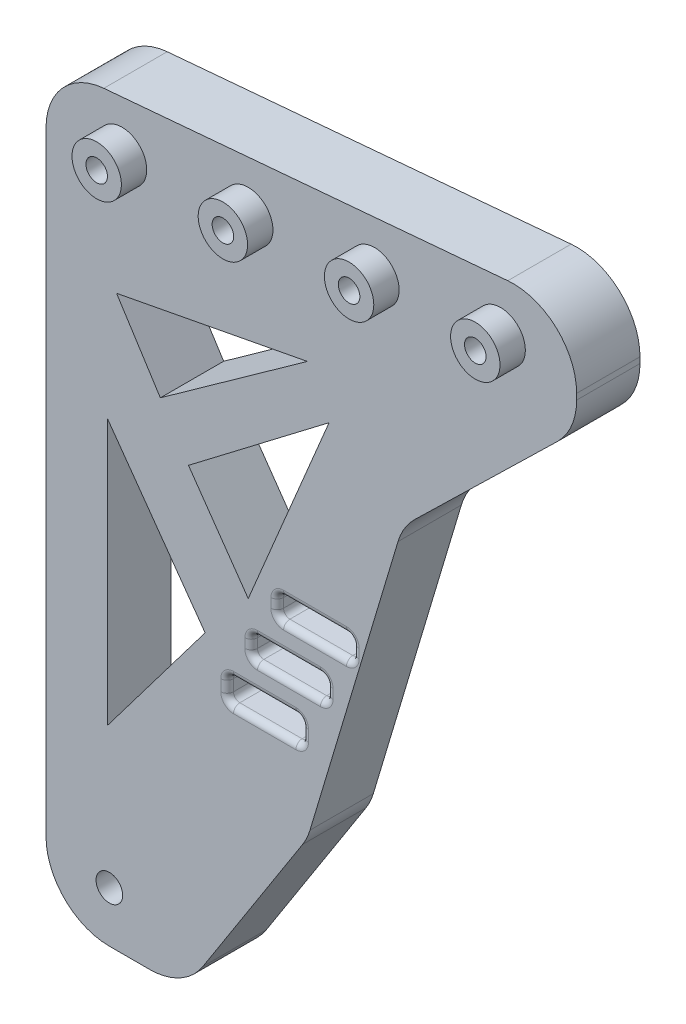
SolidWorks part; units mm, degrees
ref_plane "Front Plane" through (0, 0, 0) normal (0, 0, 1) x (1, 0, 0)
ref_plane "Top Plane" through (0, 0, 0) normal (0, 1, 0) x (1, 0, 0)
ref_plane "Right Plane" through (0, 0, 0) normal (1, 0, 0) x (0, 0, -1)
sketch "草圖1" plane through (0, 0, 0) normal (0, 0, 1) x (1, 0, 0)
  line L0 (0, 0) -> (59.7717, 5.2293) construction
  line L1 (0, 0) -> (0, 23.9784) construction
  line L2 (-12, 6.9807) -> (-12, -9.0804)
  line L3 (-12, 6.9807) -> (71.7717, 14.3098)
  line L4 (-12, -9.0804) -> (71.7717, -1.7514)
  line L5 (71.7717, 14.3098) -> (71.7717, -1.7514)
  line L6 (-12, -9.0804) -> (-12, -109.0804)
  line L7 (-12, -109.0804) -> (9.8062, -109.0804)
  line L8 (9.8062, -109.0804) -> (29.2699, -78.7271)
  line L9 (29.2699, -78.7271) -> (44.3137, -28.4865)
  line L10 (44.3137, -28.4865) -> (71.7717, -1.7514)
  line L11 (-0.8625, -19.2433) -> (29.2699, -13.4935)
  line L12 (29.2699, -13.4935) -> (6.0482, -30.0804)
  line L13 (6.0482, -30.0804) -> (-0.8625, -19.2433)
  line L14 (-2.2999, -37.0882) -> (13.1171, -58.6721)
  line L15 (13.1171, -58.6721) -> (-2.2999, -79.0539)
  line L16 (-2.2999, -79.0539) -> (-2.2999, -37.0882)
  line L23 (20.3863, -58.6721) -> (32.3185, -58.6721)
  line L24 (32.3185, -58.6721) -> (32.3185, -55.2145)
  line L25 (32.3185, -55.2145) -> (20.3863, -55.2145)
  line L26 (20.3863, -55.2145) -> (20.3863, -58.6721)
  line L27 (16.5956, -62.7059) -> (28.4375, -62.7059)
  line L28 (28.4375, -62.7059) -> (28.4375, -66.4979)
  line L29 (28.4375, -66.4979) -> (16.5956, -66.4979)
  line L30 (16.5956, -66.4979) -> (16.5956, -62.7059)
  line L31 (10.4915, -37.0882) -> (32.6885, -20.1617)
  line L32 (32.6885, -20.1617) -> (19.9239, -50.5901)
  line L33 (19.9239, -50.5901) -> (10.4915, -37.0882)
  line L34 (24.5027, -51.1166) -> (36.4348, -51.1166)
  line L35 (36.4348, -51.1166) -> (36.4348, -47.6589)
  line L36 (36.4348, -47.6589) -> (24.5027, -47.6589)
  line L37 (24.5027, -47.6589) -> (24.5027, -51.1166)
  circle A0 centre (0, 0) radius 3.9
  circle A1 centre (19.9239, 1.7431) radius 3.9
  circle A2 centre (39.8478, 3.4862) radius 3.9
  circle A3 centre (59.7717, 5.2293) radius 3.9
  circle A4 centre (-2, -101.0804) radius 2.1
  point P36 (32.6885, -20.1617)
  point P38 (19.9239, -50.5901)
  dimension "D2" = 7.8
  dimension "D12" = 4.2
  dimension "D1" = 85
  dimension "D3" = 20
  dimension "D4" = 20
  dimension "D5" = 20
  dimension "D6" = 8
  dimension "D7" = 8
  dimension "D8" = 85
  dimension "D9" = 12
  dimension "D10" = 12
  dimension "D11" = 100
  dimension "D13" = 8
  dimension "D14" = 10
extrude "填料-伸長1" add sketch "草圖1" along normal blind 10
fillet "圓角1" radius 10 7 edges at (-12, 6.9807, 5) (71.7717, 14.3098, 5) (71.7717, -1.7514, 5) (44.3137, -28.4865, 5) (29.2699, -78.7271, 5) (9.8062, -109.0804, 5) (-12, -109.0804, 5)
sketch "草圖2" plane through (0, 0, 0) normal (0, 0, 1) x (1, 0, 0)
  circle A0 centre (0, 0) radius 3.9
  circle A1 centre (0, 0) radius 1.7
  circle A2 centre (19.9239, 1.7431) radius 3.9
  circle A3 centre (19.9239, 1.7431) radius 1.7
  circle A4 centre (39.8478, 3.4862) radius 3.9
  circle A5 centre (39.8478, 3.4862) radius 1.7
  circle A6 centre (59.7717, 5.2293) radius 3.9
  circle A7 centre (59.7717, 5.2293) radius 1.7
  dimension "D1" = 3.4
extrude "填料-伸長2" add sketch "草圖2" along normal blind 14
fillet "圓角2" radius 1 36 edges at (24.5027, -49.3877, 10) (24.5027, -49.3877, 0) (36.4348, -49.3877, 10) (36.4348, -49.3877, 0) (32.3185, -56.9433, 10) (32.3185, -56.9433, 0) (20.3863, -56.9433, 10) (20.3863, -56.9433, 0) (28.4375, -64.6019, 10) (28.4375, -64.6019, 0) (16.5956, -64.6019, 10) (16.5956, -64.6019, 0) (36.4348, -51.1166, 5) (30.4688, -51.1166, 10) (24.5027, -51.1166, 5) (30.4688, -51.1166, 0) (24.5027, -47.6589, 5) (30.4688, -47.6589, 10) (36.4348, -47.6589, 5) (30.4688, -47.6589, 0) (20.3863, -55.2145, 5) (26.3524, -55.2145, 10) (32.3185, -55.2145, 5) (26.3524, -55.2145, 0) (16.5956, -62.7059, 5) (22.5166, -62.7059, 10) (28.4375, -62.7059, 5) (22.5166, -62.7059, 0) (32.3185, -58.6721, 5) (26.3524, -58.6721, 10) (20.3863, -58.6721, 5) (26.3524, -58.6721, 0) (28.4375, -66.4979, 5) (22.5166, -66.4979, 10) (16.5956, -66.4979, 5) (22.5166, -66.4979, 0)
